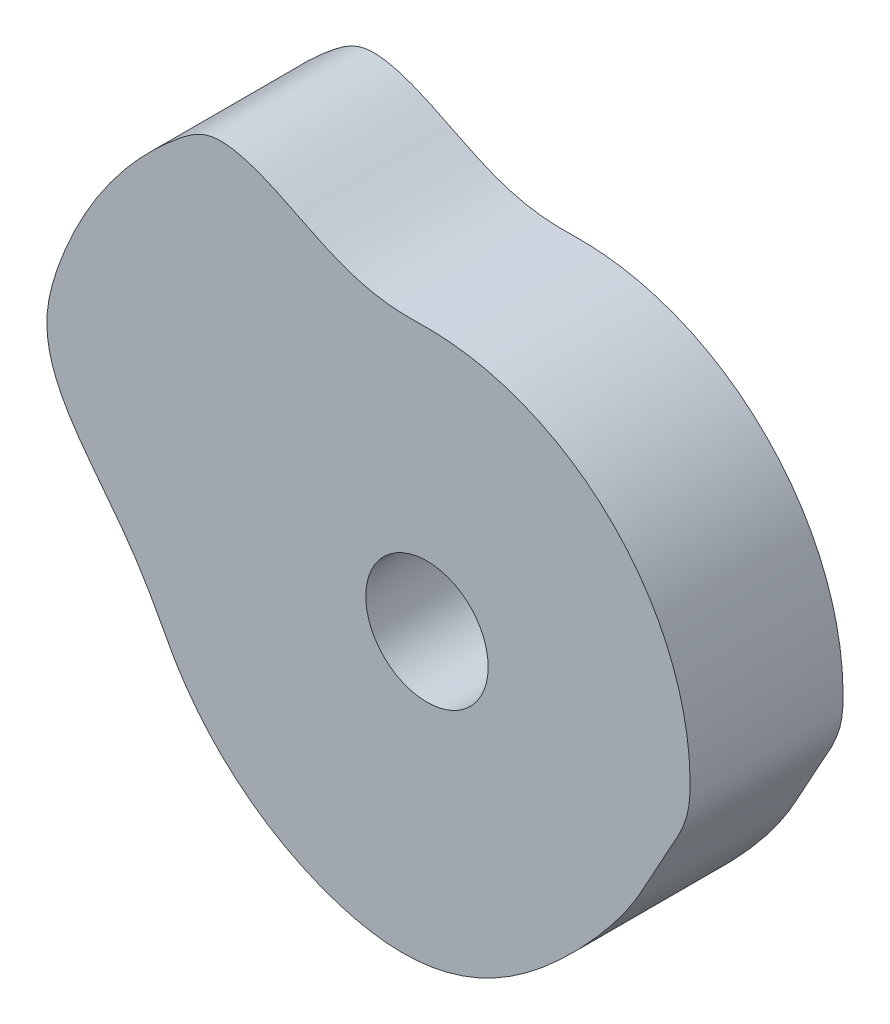
SolidWorks part; units mm, degrees
ref_plane "前视基准面" through (0, 0, 0) normal (0, 0, 1) x (1, 0, 0)
ref_plane "上视基准面" through (0, 0, 0) normal (0, 1, 0) x (1, 0, 0)
ref_plane "右视基准面" through (0, 0, 0) normal (1, 0, 0) x (0, 0, -1)
other "Configuration Table"
curve "曲线1"
sketch "草图1" plane through (0, 0, 0) normal (0, 0, 1) x (1, 0, 0)
  spline S0 degree 3 poles (0.3723, 42.999) (-0.0088, 43.0005) (-0.4074, 42.9988) (-0.8321, 42.9946) (-1.2941, 42.9895) (-1.7902, 42.9845) (-2.3194, 42.9823) (-2.8809, 42.9844) (-3.4733, 42.9934) (-4.0947, 43.0117) (-4.7431, 43.0421) (-5.4158, 43.0865) (-6.1099, 43.1475) (-6.822, 43.2268) (-7.5486, 43.3262) (-8.2858, 43.4462) (-9.0301, 43.5878) (-9.7777, 43.7508) (-10.5255, 43.9345) (-11.2705, 44.138) (-12.0104, 44.3601) (-12.7432, 44.5992) (-13.4676, 44.8538) (-14.1826, 45.1216) (-14.8878, 45.4014) (-15.5832, 45.6911) (-16.2688, 45.989) (-16.9451, 46.2936) (-17.6126, 46.6034) (-18.2719, 46.917) (-18.9237, 47.2326) (-19.5683, 47.5495) (-20.2066, 47.8659) (-20.8388, 48.1807) (-21.4653, 48.4929) (-22.0864, 48.8008) (-22.7021, 49.1035) (-23.3123, 49.3998) (-23.9171, 49.6882) (-24.5158, 49.9681) (-25.1084, 50.2376) (-25.6941, 50.4963) (-26.2722, 50.7427) (-26.8421, 50.9761) (-27.4028, 51.1954) (-27.9536, 51.3998) (-28.4933, 51.5888) (-29.0211, 51.7618) (-29.5359, 51.9181) (-30.0368, 52.0575) (-30.5227, 52.1801) (-30.9929, 52.2857) (-31.4466, 52.3748) (-31.8832, 52.4473) (-32.3023, 52.504) (-32.7036, 52.5455) (-33.0873, 52.5725) (-33.4537, 52.5858) (-33.8034, 52.5862) (-34.1374, 52.5746) (-34.4569, 52.5518) (-34.7635, 52.5182) (-35.0591, 52.4744) (-35.3455, 52.4209) (-35.6251, 52.3571) (-35.9, 52.2834) (-36.1727, 52.199) (-36.4454, 52.1033) (-36.7201, 51.9955) (-36.9992, 51.8744) (-37.2841, 51.7388) (-37.5767, 51.5877) (-37.8784, 51.4199) (-38.1902, 51.234) (-38.5133, 51.0294) (-38.8483, 50.8049) (-39.196, 50.5601) (-39.5571, 50.2945) (-39.932, 50.0077) (-40.3214, 49.6999) (-40.7256, 49.3712) (-41.1422, 49.0247) (-41.5653, 48.6666) (-41.9883, 48.302) (-42.4083, 47.9338) (-42.825, 47.5619) (-43.2383, 47.1863) (-43.6484, 46.8072) (-44.0553, 46.4246) (-44.4586, 46.0382) (-44.8588, 45.6486) (-45.2553, 45.2553) (-45.6486, 44.8588) (-46.0382, 44.4586) (-46.4246, 44.0553) (-46.8072, 43.6484) (-47.1863, 43.2383) (-47.5619, 42.825) (-47.9338, 42.4083) (-48.302, 41.9883) (-48.6666, 41.5653) (-49.0274, 41.1389) (-49.3846, 40.7096) (-49.7379, 40.277) (-50.0875, 39.8414) (-50.4334, 39.4028) (-50.7752, 38.9612) (-51.1134, 38.5167) (-51.4474, 38.0691) (-51.7778, 37.6188) (-52.1041, 37.1655) (-52.4264, 36.7093) (-52.7448, 36.2505) (-53.059, 35.7887) (-53.3694, 35.3245) (-53.6755, 34.8573) (-53.9778, 34.3877) (-54.2757, 33.9152) (-54.5697, 33.4403) (-54.8593, 32.9628) (-55.1451, 32.4829) (-55.4263, 32.0004) (-55.7035, 31.5155) (-55.9764, 31.0282) (-56.245, 30.5386) (-56.5093, 30.0465) (-56.7694, 29.5523) (-57.0251, 29.0558) (-57.2765, 28.5571) (-57.5235, 28.0561) (-57.7662, 27.5531) (-58.0044, 27.0479) (-58.2382, 26.5407) (-58.4676, 26.0315) (-58.6925, 25.5202) (-58.9131, 25.0071) (-59.129, 24.492) (-59.3406, 23.9751) (-59.5475, 23.4564) (-59.7498, 22.9358) (-59.9478, 22.4136) (-60.1405, 21.8911) (-60.3271, 21.3716) (-60.5058, 20.858) (-60.6762, 20.3517) (-60.8374, 19.8525) (-60.9898, 19.3605) (-61.1329, 18.8754) (-61.2662, 18.397) (-61.3902, 17.9252) (-61.5043, 17.4599) (-61.6087, 17.0007) (-61.7032, 16.5475) (-61.7878, 16.1) (-61.8625, 15.6578) (-61.9274, 15.2207) (-61.9825, 14.7884) (-62.0278, 14.3604) (-62.0633, 13.9363) (-62.0889, 13.5158) (-62.1049, 13.0983) (-62.1111, 12.6835) (-62.1077, 12.2709) (-62.0944, 11.8599) (-62.0712, 11.4501) (-62.0383, 11.0411) (-61.9954, 10.6324) (-61.9424, 10.2236) (-61.8794, 9.8142) (-61.806, 9.4039) (-61.7222, 8.9924) (-61.628, 8.5793) (-61.523, 8.1644) (-61.4072, 7.7475) (-61.2805, 7.3282) (-61.1427, 6.9067) (-60.9939, 6.4827) (-60.8339, 6.0561) (-60.6626, 5.6271) (-60.4802, 5.1954) (-60.2866, 4.7613) (-60.0819, 4.3247) (-59.8663, 3.8857) (-59.6397, 3.4445) (-59.4024, 3.0011) (-59.1546, 2.5557) (-58.8966, 2.1083) (-58.6286, 1.6591) (-58.351, 1.2081) (-58.064, 0.7555) (-57.7682, 0.3012) (-57.4636, -0.1543) (-57.151, -0.6115) (-56.8307, -1.0702) (-56.503, -1.5301) (-56.1686, -1.9917) (-55.8277, -2.4547) (-55.4811, -2.9192) (-55.1289, -3.3854) (-54.7721, -3.8533) (-54.4107, -4.3231) (-54.0456, -4.7949) (-53.6771, -5.2688) (-53.3058, -5.745) (-52.9324, -6.2237) (-52.5569, -6.7049) (-52.1807, -7.189) (-51.8034, -7.6757) (-51.4264, -8.1657) (-51.0497, -8.6586) (-50.6741, -9.1547) (-50.3, -9.6538) (-49.9282, -10.1561) (-49.5592, -10.6614) (-49.1932, -11.1694) (-48.8315, -11.6802) (-48.4738, -12.1931) (-48.1211, -12.7082) (-47.7739, -13.2248) (-47.4323, -13.7423) (-47.0968, -14.2603) (-46.7682, -14.7783) (-46.4461, -15.2954) (-46.1309, -15.811) (-45.8231, -16.3243) (-45.5225, -16.8346) (-45.2291, -17.3411) (-44.9431, -17.8429) (-44.664, -18.3393) (-44.3922, -18.8296) (-44.1269, -19.3128) (-43.8685, -19.7886) (-43.616, -20.2559) (-43.3698, -20.7143) (-43.1287, -21.163) (-42.8934, -21.6019) (-42.6626, -22.0299) (-42.4367, -22.4469) (-42.2149, -22.8524) (-41.997, -23.246) (-41.7828, -23.6276) (-41.5708, -23.9985) (-41.3587, -24.3621) (-41.1445, -24.7221) (-40.9272, -25.0802) (-40.7068, -25.4364) (-40.4833, -25.7907) (-40.2567, -26.143) (-40.027, -26.4933) (-39.7943, -26.8416) (-39.5586, -27.1879) (-39.3198, -27.532) (-39.0779, -27.874) (-38.8333, -28.2141) (-38.5856, -28.5518) (-38.335, -28.8875) (-38.0815, -29.2209) (-37.825, -29.5521) (-37.5657, -29.8811) (-37.3035, -30.2078) (-37.0385, -30.5322) (-36.7705, -30.8542) (-36.5, -31.1739) (-36.2265, -31.4912) (-35.9504, -31.8062) (-35.6715, -32.1187) (-35.3897, -32.4287) (-35.1055, -32.7363) (-34.8184, -33.0414) (-34.5288, -33.344) (-34.2364, -33.644) (-33.9415, -33.9415) (-33.644, -34.2364) (-33.344, -34.5288) (-33.0414, -34.8184) (-32.7363, -35.1055) (-32.4287, -35.3897) (-32.1187, -35.6715) (-31.8062, -35.9504) (-31.4912, -36.2265) (-31.1739, -36.5) (-30.8542, -36.7705) (-30.5322, -37.0385) (-30.2078, -37.3035) (-29.8811, -37.5657) (-29.5521, -37.825) (-29.2209, -38.0815) (-28.8875, -38.335) (-28.5518, -38.5856) (-28.2141, -38.8333) (-27.874, -39.0779) (-27.532, -39.3198) (-27.1879, -39.5586) (-26.8416, -39.7943) (-26.4933, -40.027) (-26.143, -40.2567) (-25.7907, -40.4833) (-25.4364, -40.7068) (-25.0802, -40.9272) (-24.7221, -41.1445) (-24.3621, -41.3587) (-24.0003, -41.5697) (-23.6367, -41.7776) (-23.2711, -41.9823) (-22.9039, -42.1837) (-22.5349, -42.382) (-22.1642, -42.577) (-21.7918, -42.7688) (-21.4177, -42.9573) (-21.0421, -43.1427) (-20.6648, -43.3246) (-20.286, -43.5034) (-19.9055, -43.6786) (-19.5237, -43.8508) (-19.1402, -44.0195) (-18.7553, -44.1847) (-18.369, -44.3468) (-17.9813, -44.5054) (-17.5923, -44.6606) (-17.2019, -44.8125) (-16.8102, -44.9609) (-16.4174, -45.1057) (-16.0242, -45.2469) (-15.6308, -45.3842) (-15.2377, -45.5174) (-14.8448, -45.6467) (-14.4522, -45.7717) (-14.0598, -45.8925) (-13.6678, -46.0093) (-13.276, -46.1215) (-12.8845, -46.2297) (-12.4934, -46.3334) (-12.1026, -46.433) (-11.7122, -46.528) (-11.3222, -46.6186) (-10.9326, -46.7048) (-10.5434, -46.7865) (-10.1546, -46.8637) (-9.7664, -46.9365) (-9.3785, -47.0045) (-8.9912, -47.0682) (-8.6044, -47.127) (-8.2181, -47.1815) (-7.8323, -47.2312) (-7.447, -47.2763) (-7.0623, -47.3167) (-6.6782, -47.3525) (-6.2947, -47.3837) (-5.9118, -47.4101) (-5.5296, -47.4317) (-5.1479, -47.4488) (-4.767, -47.4609) (-4.3866, -47.4686) (-4.007, -47.4714) (-3.628, -47.4695) (-3.2497, -47.4627) (-2.8721, -47.4515) (-2.4953, -47.4354) (-2.1192, -47.4145) (-1.7439, -47.389) (-1.3693, -47.3587) (-0.9954, -47.3237) (-0.6224, -47.284) (-0.2502, -47.2396) (0.1213, -47.1905) (0.4919, -47.1367) (0.8617, -47.0782) (1.2306, -47.015) (1.5987, -46.9471) (1.9659, -46.8748) (2.3322, -46.7976) (2.6976, -46.7161) (3.0621, -46.6297) (3.4258, -46.539) (3.7884, -46.4435) (4.1501, -46.3436) (4.5108, -46.2392) (4.8706, -46.1303) (5.2294, -46.0168) (5.5872, -45.8991) (5.9439, -45.7769) (6.2995, -45.6502) (6.6542, -45.5195) (7.0077, -45.384) (7.3602, -45.2448) (7.7116, -45.1009) (8.0619, -44.9531) (8.411, -44.8009) (8.759, -44.6447) (9.1058, -44.4845) (9.4515, -44.3202) (9.796, -44.152) (10.1393, -43.9798) (10.4813, -43.8036) (10.8222, -43.6238) (11.1618, -43.44) (11.5002, -43.2526) (11.8374, -43.0616) (12.1733, -42.8668) (12.5079, -42.6685) (12.8413, -42.4668) (13.1732, -42.2614) (13.504, -42.0529) (13.8335, -41.841) (14.1616, -41.6257) (14.4885, -41.4074) (14.814, -41.1857) (15.1383, -40.9611) (15.4612, -40.7335) (15.7827, -40.5029) (16.103, -40.2695) (16.4219, -40.0332) (16.7395, -39.7942) (17.0559, -39.5526) (17.3707, -39.3082) (17.6843, -39.0615) (17.9966, -38.8121) (18.3076, -38.5604) (18.6173, -38.3064) (18.9256, -38.0501) (19.2325, -37.7915) (19.5381, -37.5309) (19.8424, -37.2682) (20.1453, -37.0034) (20.447, -36.7368) (20.7472, -36.4682) (21.0461, -36.1979) (21.3436, -35.9258) (21.6399, -35.6521) (21.9346, -35.3767) (22.228, -35.0998) (22.52, -34.8214) (22.8106, -34.5416) (23.0998, -34.2605) (23.3875, -33.9779) (23.6738, -33.6943) (23.9586, -33.4094) (24.2419, -33.1233) (24.5236, -32.8361) (24.8039, -32.5479) (25.0825, -32.2587) (25.3596, -31.9687) (25.635, -31.6777) (25.9088, -31.3859) (26.1809, -31.0934) (26.4511, -30.7999) (26.7198, -30.506) (26.9865, -30.2113) (27.2516, -29.916) (27.5145, -29.6201) (27.7757, -29.3237) (28.0348, -29.0268) (28.2919, -28.7293) (28.547, -28.4315) (28.7999, -28.1333) (29.0507, -27.8346) (29.2993, -27.5356) (29.5456, -27.2363) (29.7896, -26.9367) (30.0312, -26.6368) (30.2706, -26.3367) (30.5071, -26.0361) (30.7415, -25.7356) (30.9731, -25.4348) (31.2021, -25.1337) (31.4284, -24.8325) (31.652, -24.5312) (31.8728, -24.2298) (32.0907, -23.9282) (32.3057, -23.6265) (32.5178, -23.3246) (32.7268, -23.0227) (32.9328, -22.7207) (33.1358, -22.4187) (33.3354, -22.1165) (33.532, -21.8144) (33.7253, -21.5122) (33.9152, -21.2099) (34.1018, -20.9076) (34.2851, -20.6054) (34.4648, -20.303) (34.6424, -19.9987) (34.8198, -19.6881) (34.9999, -19.3674) (35.184, -19.0349) (35.3721, -18.691) (35.5643, -18.3364) (35.7607, -17.9716) (35.9613, -17.5975) (36.1661, -17.215) (36.3749, -16.825) (36.5877, -16.4287) (36.8042, -16.027) (37.0241, -15.6211) (37.2468, -15.2121) (37.4723, -14.8014) (37.6995, -14.3898) (37.9284, -13.9787) (38.1577, -13.5688) (38.3874, -13.1614) (38.6162, -12.7573) (38.8434, -12.3573) (39.0685, -11.9622) (39.2907, -11.5727) (39.509, -11.1893) (39.7228, -10.8125) (39.9315, -10.4427) (40.1344, -10.0803) (40.3308, -9.7255) (40.5204, -9.3786) (40.7028, -9.0395) (40.8774, -8.7083) (41.0443, -8.3852) (41.2027, -8.0698) (41.353, -7.7621) (41.4952, -7.4621) (41.6289, -7.1691) (41.7546, -6.8829) (41.8723, -6.6032) (41.9821, -6.3292) (42.0847, -6.0606) (42.1801, -5.7965) (42.2686, -5.5361) (42.3508, -5.2787) (42.4267, -5.0231) (42.497, -4.7686) (42.5619, -4.5139) (42.6214, -4.2581) (42.6762, -4) (42.7263, -3.7385) (42.7718, -3.4725) (42.813, -3.201) (42.8499, -2.9229) (42.8826, -2.6373) (42.9111, -2.3433) (42.9358, -2.0401) (42.9562, -1.727) (42.9726, -1.4034) (42.9851, -1.0688) (42.994, -0.7229) (42.9989, -0.3653) (43.0005, 0.002) (42.9989, 0.3752) (42.994, 0.7505) (42.9859, 1.1256) (42.9743, 1.5007) (42.9597, 1.8756) (42.9417, 2.2505) (42.9203, 2.6251) (42.8959, 2.9996) (42.8679, 3.3738) (42.837, 3.7478) (42.8025, 4.1214) (42.7649, 4.4948) (42.7241, 4.8678) (42.6801, 5.2404) (42.6326, 5.6127) (42.582, 5.9845) (42.5283, 6.3559) (42.4711, 6.7268) (42.4109, 7.0971) (42.3472, 7.4669) (42.2806, 7.8362) (42.2105, 8.2049) (42.1374, 8.5729) (42.0608, 8.9403) (41.9812, 9.307) (41.8984, 9.673) (41.8125, 10.0383) (41.7232, 10.4028) (41.6308, 10.7664) (41.5353, 11.1294) (41.4366, 11.4914) (41.3349, 11.8526) (41.2297, 12.2128) (41.1217, 12.5722) (41.0103, 12.9305) (40.8959, 13.2879) (40.7784, 13.6443) (40.6578, 13.9996) (40.5341, 14.3539) (40.4073, 14.7071) (40.2774, 15.0591) (40.1445, 15.41) (40.0085, 15.7598) (39.8694, 16.1083) (39.7273, 16.4556) (39.5822, 16.8016) (39.4341, 17.1464) (39.283, 17.4899) (39.1288, 17.832) (38.9717, 18.1728) (38.8117, 18.5123) (38.6486, 18.8502) (38.4827, 19.1868) (38.3138, 19.5218) (38.142, 19.8555) (37.9672, 20.1875) (37.7896, 20.5181) (37.6091, 20.847) (37.4258, 21.1745) (37.2396, 21.5002) (37.0506, 21.8244) (36.8587, 22.1469) (36.6639, 22.4677) (36.4666, 22.7868) (36.2663, 23.1042) (36.0633, 23.4198) (35.8576, 23.7336) (35.649, 24.0456) (35.4379, 24.3558) (35.2239, 24.6641) (35.0074, 24.9706) (34.7882, 25.2751) (34.5663, 25.5777) (34.3417, 25.8783) (34.1146, 26.177) (33.8849, 26.4737) (33.6526, 26.7685) (33.4177, 27.0611) (33.1803, 27.3518) (32.9403, 27.6402) (32.698, 27.9267) (32.4528, 28.2108) (32.2056, 28.4931) (31.9556, 28.7729) (31.7033, 29.0508) (31.4486, 29.3263) (31.1915, 29.5996) (30.932, 29.8707) (30.6702, 30.1395) (30.406, 30.406) (30.1395, 30.6702) (29.8707, 30.932) (29.5996, 31.1915) (29.3263, 31.4486) (29.0508, 31.7033) (28.7729, 31.9556) (28.4931, 32.2056) (28.2108, 32.4528) (27.9267, 32.698) (27.6402, 32.9403) (27.3518, 33.1803) (27.0611, 33.4177) (26.7685, 33.6526) (26.4737, 33.8849) (26.177, 34.1146) (25.8783, 34.3417) (25.5777, 34.5663) (25.2751, 34.7882) (24.9706, 35.0074) (24.6641, 35.2239) (24.3558, 35.4379) (24.0456, 35.649) (23.7336, 35.8576) (23.4198, 36.0633) (23.1042, 36.2663) (22.7868, 36.4666) (22.4677, 36.6639) (22.1469, 36.8587) (21.8244, 37.0506) (21.5002, 37.2396) (21.1745, 37.4258) (20.847, 37.6091) (20.5181, 37.7896) (20.1875, 37.9672) (19.8555, 38.142) (19.5218, 38.3138) (19.1868, 38.4827) (18.8502, 38.6486) (18.5123, 38.8117) (18.1728, 38.9717) (17.832, 39.1288) (17.4899, 39.283) (17.1464, 39.4341) (16.8016, 39.5822) (16.4556, 39.7273) (16.1083, 39.8694) (15.7598, 40.0085) (15.41, 40.1445) (15.0591, 40.2774) (14.7071, 40.4073) (14.3539, 40.5341) (13.9996, 40.6578) (13.6443, 40.7784) (13.2879, 40.8959) (12.9305, 41.0103) (12.5722, 41.1217) (12.2128, 41.2297) (11.8526, 41.3349) (11.4914, 41.4366) (11.1294, 41.5353) (10.7664, 41.6308) (10.4028, 41.7232) (10.0383, 41.8125) (9.673, 41.8984) (9.307, 41.9812) (8.9403, 42.0608) (8.5729, 42.1374) (8.2049, 42.2105) (7.8362, 42.2806) (7.4669, 42.3472) (7.0971, 42.4109) (6.7268, 42.4711) (6.3559, 42.5283) (5.9845, 42.582) (5.6127, 42.6326) (5.2404, 42.6801) (4.8678, 42.7241) (4.4948, 42.7649) (4.1214, 42.8025) (3.7478, 42.837) (3.3738, 42.8679) (2.9996, 42.8959) (2.6251, 42.9203) (2.2505, 42.9417) (1.8756, 42.9597) (1.5007, 42.9743) (1.1256, 42.9859) (0.7505, 42.994) (0.3723, 42.999) (-0.0088, 43.0005) (-0.4074, 42.9988) knots -0.003606 -0.002413 -0.00122 0 0.001222 0.002581 0.00405 0.005628 0.007311 0.009098 0.010982 0.012961 0.015026 0.017172 0.01939 0.02167 0.024004 0.026382 0.028793 0.031228 0.033678 0.036135 0.038593 0.041044 0.043486 0.045914 0.048326 0.050721 0.053097 0.055455 0.057794 0.060115 0.062417 0.0647 0.066965 0.06921 0.071436 0.07364 0.075821 0.077978 0.080109 0.082211 0.084281 0.086317 0.088316 0.090274 0.092189 0.094058 0.095877 0.097643 0.099354 0.101007 0.1026 0.104133 0.105602 0.107009 0.108353 0.109634 0.110856 0.11202 0.11313 0.11419 0.115206 0.116184 0.117131 0.118055 0.118963 0.119865 0.120769 0.121684 0.122619 0.123583 0.124584 0.125628 0.126724 0.127876 0.129089 0.13037 0.131721 0.133145 0.134645 0.136222 0.137878 0.139613 0.141388 0.143164 0.144939 0.146715 0.14849 0.150265 0.152041 0.153816 0.155592 0.157367 0.159142 0.160918 0.162693 0.164468 0.166244 0.168019 0.169795 0.17157 0.173345 0.175121 0.176896 0.178671 0.180447 0.182222 0.183998 0.185773 0.187548 0.189324 0.191099 0.192874 0.19465 0.196425 0.1982 0.199976 0.201751 0.203527 0.205302 0.207078 0.208853 0.210628 0.212404 0.214179 0.215954 0.21773 0.219505 0.22128 0.223056 0.224831 0.226607 0.228382 0.230157 0.231933 0.233708 0.235483 0.237259 0.239034 0.24081 0.242585 0.24436 0.246136 0.247895 0.249624 0.251322 0.252989 0.254627 0.256234 0.257812 0.259363 0.260885 0.262382 0.263853 0.2653 0.266725 0.268129 0.269514 0.270881 0.272233 0.273571 0.274899 0.276216 0.277527 0.278834 0.280137 0.281441 0.282746 0.284056 0.285372 0.286696 0.28803 0.289376 0.290736 0.292111 0.293503 0.294912 0.29634 0.297788 0.299256 0.300746 0.302257 0.303789 0.305344 0.30692 0.308519 0.310139 0.311781 0.313444 0.315128 0.316831 0.318555 0.320297 0.322058 0.323836 0.325632 0.327443 0.329271 0.331114 0.332971 0.334842 0.336727 0.338623 0.340532 0.342451 0.344382 0.346322 0.348271 0.350229 0.352194 0.354167 0.356145 0.358128 0.360115 0.362105 0.364095 0.366086 0.368074 0.370059 0.372038 0.37401 0.375972 0.377923 0.379861 0.381782 0.383685 0.385569 0.38743 0.389267 0.391077 0.39286 0.394613 0.396335 0.398023 0.399678 0.401297 0.402881 0.404427 0.405934 0.407404 0.408834 0.410225 0.411577 0.412908 0.41424 0.415571 0.416903 0.418234 0.419566 0.420897 0.422229 0.42356 0.424892 0.426223 0.427555 0.428887 0.430218 0.431549 0.432881 0.434213 0.435544 0.436876 0.438207 0.439539 0.44087 0.442202 0.443533 0.444865 0.446196 0.447528 0.44886 0.450191 0.451523 0.452854 0.454186 0.455517 0.456849 0.45818 0.459512 0.460843 0.462175 0.463506 0.464838 0.466169 0.467501 0.468833 0.470164 0.471496 0.472827 0.474159 0.47549 0.476822 0.478153 0.479485 0.480816 0.482148 0.483479 0.484811 0.486143 0.487474 0.488806 0.490137 0.491469 0.4928 0.494132 0.495463 0.496795 0.498126 0.499458 0.500789 0.502121 0.503453 0.504784 0.506115 0.507447 0.508778 0.51011 0.511442 0.512773 0.514105 0.515436 0.516768 0.518099 0.519428 0.520753 0.522072 0.523387 0.524697 0.526001 0.527302 0.528597 0.529888 0.531175 0.532456 0.533734 0.535006 0.536275 0.537539 0.538799 0.540054 0.541306 0.542554 0.543797 0.545038 0.546274 0.547507 0.548737 0.549963 0.551186 0.552406 0.553623 0.554837 0.556049 0.557258 0.558465 0.559669 0.560872 0.562072 0.563271 0.564469 0.565664 0.566859 0.568053 0.569245 0.570436 0.571627 0.572818 0.574008 0.575198 0.576387 0.577577 0.578767 0.579957 0.581148 0.582339 0.583531 0.584724 0.585917 0.587112 0.588308 0.589506 0.590704 0.591904 0.593106 0.594309 0.595514 0.596721 0.597929 0.59914 0.600352 0.601567 0.602783 0.604002 0.605223 0.606446 0.607671 0.608898 0.610128 0.61136 0.612594 0.613831 0.615069 0.61631 0.617553 0.618798 0.620046 0.621295 0.622547 0.623801 0.625057 0.626315 0.627574 0.628836 0.6301 0.631365 0.632632 0.633901 0.635171 0.636443 0.637716 0.63899 0.640266 0.641543 0.642821 0.6441 0.645379 0.64666 0.647941 0.649223 0.650505 0.651787 0.65307 0.654352 0.655635 0.656917 0.658199 0.65948 0.66076 0.66204 0.663319 0.664597 0.665874 0.667149 0.668422 0.669694 0.670965 0.672233 0.673499 0.674762 0.676024 0.677282 0.678538 0.679791 0.68104 0.682287 0.68353 0.68477 0.686006 0.687238 0.688466 0.689691 0.690911 0.692127 0.693338 0.694545 0.695748 0.696945 0.698138 0.699326 0.700509 0.701686 0.702859 0.704026 0.705188 0.706345 0.707496 0.708642 0.709783 0.710917 0.712046 0.71317 0.714288 0.715401 0.71653 0.7177 0.718908 0.720154 0.721437 0.722755 0.724105 0.725486 0.726893 0.728324 0.729776 0.731244 0.732726 0.734217 0.735712 0.73721 0.738704 0.740192 0.741669 0.743133 0.744579 0.746005 0.747409 0.748787 0.750137 0.751458 0.752747 0.754004 0.755229 0.756419 0.757575 0.758697 0.759785 0.76084 0.761863 0.762856 0.76382 0.764757 0.765671 0.766562 0.767435 0.768293 0.769139 0.769977 0.770811 0.771645 0.772482 0.773327 0.774184 0.775056 0.775946 0.776859 0.777797 0.778763 0.779759 0.780789 0.781853 0.782952 0.784089 0.785263 0.786455 0.787648 0.788841 0.790034 0.791227 0.792419 0.793613 0.794805 0.795998 0.797191 0.798384 0.799577 0.800769 0.801962 0.803155 0.804348 0.805541 0.806734 0.807926 0.809119 0.810312 0.811505 0.812698 0.813891 0.815083 0.816276 0.817469 0.818662 0.819855 0.821048 0.822241 0.823433 0.824626 0.825819 0.827012 0.828205 0.829397 0.83059 0.831783 0.832976 0.834169 0.835361 0.836554 0.837747 0.83894 0.840133 0.841326 0.842519 0.843711 0.844904 0.846097 0.84729 0.848483 0.849676 0.850868 0.852061 0.853254 0.854447 0.85564 0.856833 0.858025 0.859218 0.860411 0.861604 0.862797 0.86399 0.865182 0.866375 0.867568 0.868761 0.869954 0.871147 0.872339 0.873532 0.874725 0.875918 0.877111 0.878304 0.879496 0.880689 0.881882 0.883075 0.884268 0.885461 0.886653 0.887846 0.889039 0.890232 0.891425 0.892617 0.89381 0.895003 0.896196 0.897389 0.898582 0.899774 0.900967 0.90216 0.903353 0.904546 0.905739 0.906931 0.908124 0.909317 0.91051 0.911703 0.912895 0.914088 0.915281 0.916474 0.917667 0.91886 0.920053 0.921245 0.922438 0.923631 0.924824 0.926017 0.92721 0.928402 0.929595 0.930788 0.931981 0.933174 0.934367 0.935559 0.936752 0.937945 0.939138 0.940331 0.941524 0.942716 0.943909 0.945102 0.946295 0.947488 0.94868 0.949874 0.951066 0.952259 0.953452 0.954645 0.955838 0.95703 0.958223 0.959416 0.960609 0.961802 0.962994 0.964187 0.96538 0.966573 0.967766 0.968959 0.970152 0.971344 0.972537 0.97373 0.974923 0.976116 0.977309 0.978501 0.979694 0.980887 0.98208 0.983273 0.984466 0.985658 0.986851 0.988044 0.989237 0.99043 0.991622 0.992816 0.994008 0.995201 0.996394 0.997587 0.99878 1 1.001222 1.002581 1.00405 only from (-0.0087, 43) to (-0.0087, 43) construction
  spline S1 degree 3 poles (0.3723, 42.999) (-0.0088, 43.0005) (-0.4074, 42.9988) (-0.8321, 42.9946) (-1.2941, 42.9895) (-1.7902, 42.9845) (-2.3194, 42.9823) (-2.8809, 42.9844) (-3.4733, 42.9934) (-4.0947, 43.0117) (-4.7431, 43.0421) (-5.4158, 43.0865) (-6.1099, 43.1475) (-6.822, 43.2268) (-7.5486, 43.3262) (-8.2858, 43.4462) (-9.0301, 43.5878) (-9.7777, 43.7508) (-10.5255, 43.9345) (-11.2705, 44.138) (-12.0104, 44.3601) (-12.7432, 44.5992) (-13.4676, 44.8538) (-14.1826, 45.1216) (-14.8878, 45.4014) (-15.5832, 45.6911) (-16.2688, 45.989) (-16.9451, 46.2936) (-17.6126, 46.6034) (-18.2719, 46.917) (-18.9237, 47.2326) (-19.5683, 47.5495) (-20.2066, 47.8659) (-20.8388, 48.1807) (-21.4653, 48.4929) (-22.0864, 48.8008) (-22.7021, 49.1035) (-23.3123, 49.3998) (-23.9171, 49.6882) (-24.5158, 49.9681) (-25.1084, 50.2376) (-25.6941, 50.4963) (-26.2722, 50.7427) (-26.8421, 50.9761) (-27.4028, 51.1954) (-27.9536, 51.3998) (-28.4933, 51.5888) (-29.0211, 51.7618) (-29.5359, 51.9181) (-30.0368, 52.0575) (-30.5227, 52.1801) (-30.9929, 52.2857) (-31.4466, 52.3748) (-31.8832, 52.4473) (-32.3023, 52.504) (-32.7036, 52.5455) (-33.0873, 52.5725) (-33.4537, 52.5858) (-33.8034, 52.5862) (-34.1374, 52.5746) (-34.4569, 52.5518) (-34.7635, 52.5182) (-35.0591, 52.4744) (-35.3455, 52.4209) (-35.6251, 52.3571) (-35.9, 52.2834) (-36.1727, 52.199) (-36.4454, 52.1033) (-36.7201, 51.9955) (-36.9992, 51.8744) (-37.2841, 51.7388) (-37.5767, 51.5877) (-37.8784, 51.4199) (-38.1902, 51.234) (-38.5133, 51.0294) (-38.8483, 50.8049) (-39.196, 50.5601) (-39.5571, 50.2945) (-39.932, 50.0077) (-40.3214, 49.6999) (-40.7256, 49.3712) (-41.1422, 49.0247) (-41.5653, 48.6666) (-41.9883, 48.302) (-42.4083, 47.9338) (-42.825, 47.5619) (-43.2383, 47.1863) (-43.6484, 46.8072) (-44.0553, 46.4246) (-44.4586, 46.0382) (-44.8588, 45.6486) (-45.2553, 45.2553) (-45.6486, 44.8588) (-46.0382, 44.4586) (-46.4246, 44.0553) (-46.8072, 43.6484) (-47.1863, 43.2383) (-47.5619, 42.825) (-47.9338, 42.4083) (-48.302, 41.9883) (-48.6666, 41.5653) (-49.0274, 41.1389) (-49.3846, 40.7096) (-49.7379, 40.277) (-50.0875, 39.8414) (-50.4334, 39.4028) (-50.7752, 38.9612) (-51.1134, 38.5167) (-51.4474, 38.0691) (-51.7778, 37.6188) (-52.1041, 37.1655) (-52.4264, 36.7093) (-52.7448, 36.2505) (-53.059, 35.7887) (-53.3694, 35.3245) (-53.6755, 34.8573) (-53.9778, 34.3877) (-54.2757, 33.9152) (-54.5697, 33.4403) (-54.8593, 32.9628) (-55.1451, 32.4829) (-55.4263, 32.0004) (-55.7035, 31.5155) (-55.9764, 31.0282) (-56.245, 30.5386) (-56.5093, 30.0465) (-56.7694, 29.5523) (-57.0251, 29.0558) (-57.2765, 28.5571) (-57.5235, 28.0561) (-57.7662, 27.5531) (-58.0044, 27.0479) (-58.2382, 26.5407) (-58.4676, 26.0315) (-58.6925, 25.5202) (-58.9131, 25.0071) (-59.129, 24.492) (-59.3406, 23.9751) (-59.5475, 23.4564) (-59.7498, 22.9358) (-59.9478, 22.4136) (-60.1405, 21.8911) (-60.3271, 21.3716) (-60.5058, 20.858) (-60.6762, 20.3517) (-60.8374, 19.8525) (-60.9898, 19.3605) (-61.1329, 18.8754) (-61.2662, 18.397) (-61.3902, 17.9252) (-61.5043, 17.4599) (-61.6087, 17.0007) (-61.7032, 16.5475) (-61.7878, 16.1) (-61.8625, 15.6578) (-61.9274, 15.2207) (-61.9825, 14.7884) (-62.0278, 14.3604) (-62.0633, 13.9363) (-62.0889, 13.5158) (-62.1049, 13.0983) (-62.1111, 12.6835) (-62.1077, 12.2709) (-62.0944, 11.8599) (-62.0712, 11.4501) (-62.0383, 11.0411) (-61.9954, 10.6324) (-61.9424, 10.2236) (-61.8794, 9.8142) (-61.806, 9.4039) (-61.7222, 8.9924) (-61.628, 8.5793) (-61.523, 8.1644) (-61.4072, 7.7475) (-61.2805, 7.3282) (-61.1427, 6.9067) (-60.9939, 6.4827) (-60.8339, 6.0561) (-60.6626, 5.6271) (-60.4802, 5.1954) (-60.2866, 4.7613) (-60.0819, 4.3247) (-59.8663, 3.8857) (-59.6397, 3.4445) (-59.4024, 3.0011) (-59.1546, 2.5557) (-58.8966, 2.1083) (-58.6286, 1.6591) (-58.351, 1.2081) (-58.064, 0.7555) (-57.7682, 0.3012) (-57.4636, -0.1543) (-57.151, -0.6115) (-56.8307, -1.0702) (-56.503, -1.5301) (-56.1686, -1.9917) (-55.8277, -2.4547) (-55.4811, -2.9192) (-55.1289, -3.3854) (-54.7721, -3.8533) (-54.4107, -4.3231) (-54.0456, -4.7949) (-53.6771, -5.2688) (-53.3058, -5.745) (-52.9324, -6.2237) (-52.5569, -6.7049) (-52.1807, -7.189) (-51.8034, -7.6757) (-51.4264, -8.1657) (-51.0497, -8.6586) (-50.6741, -9.1547) (-50.3, -9.6538) (-49.9282, -10.1561) (-49.5592, -10.6614) (-49.1932, -11.1694) (-48.8315, -11.6802) (-48.4738, -12.1931) (-48.1211, -12.7082) (-47.7739, -13.2248) (-47.4323, -13.7423) (-47.0968, -14.2603) (-46.7682, -14.7783) (-46.4461, -15.2954) (-46.1309, -15.811) (-45.8231, -16.3243) (-45.5225, -16.8346) (-45.2291, -17.3411) (-44.9431, -17.8429) (-44.664, -18.3393) (-44.3922, -18.8296) (-44.1269, -19.3128) (-43.8685, -19.7886) (-43.616, -20.2559) (-43.3698, -20.7143) (-43.1287, -21.163) (-42.8934, -21.6019) (-42.6626, -22.0299) (-42.4367, -22.4469) (-42.2149, -22.8524) (-41.997, -23.246) (-41.7828, -23.6276) (-41.5708, -23.9985) (-41.3587, -24.3621) (-41.1445, -24.7221) (-40.9272, -25.0802) (-40.7068, -25.4364) (-40.4833, -25.7907) (-40.2567, -26.143) (-40.027, -26.4933) (-39.7943, -26.8416) (-39.5586, -27.1879) (-39.3198, -27.532) (-39.0779, -27.874) (-38.8333, -28.2141) (-38.5856, -28.5518) (-38.335, -28.8875) (-38.0815, -29.2209) (-37.825, -29.5521) (-37.5657, -29.8811) (-37.3035, -30.2078) (-37.0385, -30.5322) (-36.7705, -30.8542) (-36.5, -31.1739) (-36.2265, -31.4912) (-35.9504, -31.8062) (-35.6715, -32.1187) (-35.3897, -32.4287) (-35.1055, -32.7363) (-34.8184, -33.0414) (-34.5288, -33.344) (-34.2364, -33.644) (-33.9415, -33.9415) (-33.644, -34.2364) (-33.344, -34.5288) (-33.0414, -34.8184) (-32.7363, -35.1055) (-32.4287, -35.3897) (-32.1187, -35.6715) (-31.8062, -35.9504) (-31.4912, -36.2265) (-31.1739, -36.5) (-30.8542, -36.7705) (-30.5322, -37.0385) (-30.2078, -37.3035) (-29.8811, -37.5657) (-29.5521, -37.825) (-29.2209, -38.0815) (-28.8875, -38.335) (-28.5518, -38.5856) (-28.2141, -38.8333) (-27.874, -39.0779) (-27.532, -39.3198) (-27.1879, -39.5586) (-26.8416, -39.7943) (-26.4933, -40.027) (-26.143, -40.2567) (-25.7907, -40.4833) (-25.4364, -40.7068) (-25.0802, -40.9272) (-24.7221, -41.1445) (-24.3621, -41.3587) (-24.0003, -41.5697) (-23.6367, -41.7776) (-23.2711, -41.9823) (-22.9039, -42.1837) (-22.5349, -42.382) (-22.1642, -42.577) (-21.7918, -42.7688) (-21.4177, -42.9573) (-21.0421, -43.1427) (-20.6648, -43.3246) (-20.286, -43.5034) (-19.9055, -43.6786) (-19.5237, -43.8508) (-19.1402, -44.0195) (-18.7553, -44.1847) (-18.369, -44.3468) (-17.9813, -44.5054) (-17.5923, -44.6606) (-17.2019, -44.8125) (-16.8102, -44.9609) (-16.4174, -45.1057) (-16.0242, -45.2469) (-15.6308, -45.3842) (-15.2377, -45.5174) (-14.8448, -45.6467) (-14.4522, -45.7717) (-14.0598, -45.8925) (-13.6678, -46.0093) (-13.276, -46.1215) (-12.8845, -46.2297) (-12.4934, -46.3334) (-12.1026, -46.433) (-11.7122, -46.528) (-11.3222, -46.6186) (-10.9326, -46.7048) (-10.5434, -46.7865) (-10.1546, -46.8637) (-9.7664, -46.9365) (-9.3785, -47.0045) (-8.9912, -47.0682) (-8.6044, -47.127) (-8.2181, -47.1815) (-7.8323, -47.2312) (-7.447, -47.2763) (-7.0623, -47.3167) (-6.6782, -47.3525) (-6.2947, -47.3837) (-5.9118, -47.4101) (-5.5296, -47.4317) (-5.1479, -47.4488) (-4.767, -47.4609) (-4.3866, -47.4686) (-4.007, -47.4714) (-3.628, -47.4695) (-3.2497, -47.4627) (-2.8721, -47.4515) (-2.4953, -47.4354) (-2.1192, -47.4145) (-1.7439, -47.389) (-1.3693, -47.3587) (-0.9954, -47.3237) (-0.6224, -47.284) (-0.2502, -47.2396) (0.1213, -47.1905) (0.4919, -47.1367) (0.8617, -47.0782) (1.2306, -47.015) (1.5987, -46.9471) (1.9659, -46.8748) (2.3322, -46.7976) (2.6976, -46.7161) (3.0621, -46.6297) (3.4258, -46.539) (3.7884, -46.4435) (4.1501, -46.3436) (4.5108, -46.2392) (4.8706, -46.1303) (5.2294, -46.0168) (5.5872, -45.8991) (5.9439, -45.7769) (6.2995, -45.6502) (6.6542, -45.5195) (7.0077, -45.384) (7.3602, -45.2448) (7.7116, -45.1009) (8.0619, -44.9531) (8.411, -44.8009) (8.759, -44.6447) (9.1058, -44.4845) (9.4515, -44.3202) (9.796, -44.152) (10.1393, -43.9798) (10.4813, -43.8036) (10.8222, -43.6238) (11.1618, -43.44) (11.5002, -43.2526) (11.8374, -43.0616) (12.1733, -42.8668) (12.5079, -42.6685) (12.8413, -42.4668) (13.1732, -42.2614) (13.504, -42.0529) (13.8335, -41.841) (14.1616, -41.6257) (14.4885, -41.4074) (14.814, -41.1857) (15.1383, -40.9611) (15.4612, -40.7335) (15.7827, -40.5029) (16.103, -40.2695) (16.4219, -40.0332) (16.7395, -39.7942) (17.0559, -39.5526) (17.3707, -39.3082) (17.6843, -39.0615) (17.9966, -38.8121) (18.3076, -38.5604) (18.6173, -38.3064) (18.9256, -38.0501) (19.2325, -37.7915) (19.5381, -37.5309) (19.8424, -37.2682) (20.1453, -37.0034) (20.447, -36.7368) (20.7472, -36.4682) (21.0461, -36.1979) (21.3436, -35.9258) (21.6399, -35.6521) (21.9346, -35.3767) (22.228, -35.0998) (22.52, -34.8214) (22.8106, -34.5416) (23.0998, -34.2605) (23.3875, -33.9779) (23.6738, -33.6943) (23.9586, -33.4094) (24.2419, -33.1233) (24.5236, -32.8361) (24.8039, -32.5479) (25.0825, -32.2587) (25.3596, -31.9687) (25.635, -31.6777) (25.9088, -31.3859) (26.1809, -31.0934) (26.4511, -30.7999) (26.7198, -30.506) (26.9865, -30.2113) (27.2516, -29.916) (27.5145, -29.6201) (27.7757, -29.3237) (28.0348, -29.0268) (28.2919, -28.7293) (28.547, -28.4315) (28.7999, -28.1333) (29.0507, -27.8346) (29.2993, -27.5356) (29.5456, -27.2363) (29.7896, -26.9367) (30.0312, -26.6368) (30.2706, -26.3367) (30.5071, -26.0361) (30.7415, -25.7356) (30.9731, -25.4348) (31.2021, -25.1337) (31.4284, -24.8325) (31.652, -24.5312) (31.8728, -24.2298) (32.0907, -23.9282) (32.3057, -23.6265) (32.5178, -23.3246) (32.7268, -23.0227) (32.9328, -22.7207) (33.1358, -22.4187) (33.3354, -22.1165) (33.532, -21.8144) (33.7253, -21.5122) (33.9152, -21.2099) (34.1018, -20.9076) (34.2851, -20.6054) (34.4648, -20.303) (34.6424, -19.9987) (34.8198, -19.6881) (34.9999, -19.3674) (35.184, -19.0349) (35.3721, -18.691) (35.5643, -18.3364) (35.7607, -17.9716) (35.9613, -17.5975) (36.1661, -17.215) (36.3749, -16.825) (36.5877, -16.4287) (36.8042, -16.027) (37.0241, -15.6211) (37.2468, -15.2121) (37.4723, -14.8014) (37.6995, -14.3898) (37.9284, -13.9787) (38.1577, -13.5688) (38.3874, -13.1614) (38.6162, -12.7573) (38.8434, -12.3573) (39.0685, -11.9622) (39.2907, -11.5727) (39.509, -11.1893) (39.7228, -10.8125) (39.9315, -10.4427) (40.1344, -10.0803) (40.3308, -9.7255) (40.5204, -9.3786) (40.7028, -9.0395) (40.8774, -8.7083) (41.0443, -8.3852) (41.2027, -8.0698) (41.353, -7.7621) (41.4952, -7.4621) (41.6289, -7.1691) (41.7546, -6.8829) (41.8723, -6.6032) (41.9821, -6.3292) (42.0847, -6.0606) (42.1801, -5.7965) (42.2686, -5.5361) (42.3508, -5.2787) (42.4267, -5.0231) (42.497, -4.7686) (42.5619, -4.5139) (42.6214, -4.2581) (42.6762, -4) (42.7263, -3.7385) (42.7718, -3.4725) (42.813, -3.201) (42.8499, -2.9229) (42.8826, -2.6373) (42.9111, -2.3433) (42.9358, -2.0401) (42.9562, -1.727) (42.9726, -1.4034) (42.9851, -1.0688) (42.994, -0.7229) (42.9989, -0.3653) (43.0005, 0.002) (42.9989, 0.3752) (42.994, 0.7505) (42.9859, 1.1256) (42.9743, 1.5007) (42.9597, 1.8756) (42.9417, 2.2505) (42.9203, 2.6251) (42.8959, 2.9996) (42.8679, 3.3738) (42.837, 3.7478) (42.8025, 4.1214) (42.7649, 4.4948) (42.7241, 4.8678) (42.6801, 5.2404) (42.6326, 5.6127) (42.582, 5.9845) (42.5283, 6.3559) (42.4711, 6.7268) (42.4109, 7.0971) (42.3472, 7.4669) (42.2806, 7.8362) (42.2105, 8.2049) (42.1374, 8.5729) (42.0608, 8.9403) (41.9812, 9.307) (41.8984, 9.673) (41.8125, 10.0383) (41.7232, 10.4028) (41.6308, 10.7664) (41.5353, 11.1294) (41.4366, 11.4914) (41.3349, 11.8526) (41.2297, 12.2128) (41.1217, 12.5722) (41.0103, 12.9305) (40.8959, 13.2879) (40.7784, 13.6443) (40.6578, 13.9996) (40.5341, 14.3539) (40.4073, 14.7071) (40.2774, 15.0591) (40.1445, 15.41) (40.0085, 15.7598) (39.8694, 16.1083) (39.7273, 16.4556) (39.5822, 16.8016) (39.4341, 17.1464) (39.283, 17.4899) (39.1288, 17.832) (38.9717, 18.1728) (38.8117, 18.5123) (38.6486, 18.8502) (38.4827, 19.1868) (38.3138, 19.5218) (38.142, 19.8555) (37.9672, 20.1875) (37.7896, 20.5181) (37.6091, 20.847) (37.4258, 21.1745) (37.2396, 21.5002) (37.0506, 21.8244) (36.8587, 22.1469) (36.6639, 22.4677) (36.4666, 22.7868) (36.2663, 23.1042) (36.0633, 23.4198) (35.8576, 23.7336) (35.649, 24.0456) (35.4379, 24.3558) (35.2239, 24.6641) (35.0074, 24.9706) (34.7882, 25.2751) (34.5663, 25.5777) (34.3417, 25.8783) (34.1146, 26.177) (33.8849, 26.4737) (33.6526, 26.7685) (33.4177, 27.0611) (33.1803, 27.3518) (32.9403, 27.6402) (32.698, 27.9267) (32.4528, 28.2108) (32.2056, 28.4931) (31.9556, 28.7729) (31.7033, 29.0508) (31.4486, 29.3263) (31.1915, 29.5996) (30.932, 29.8707) (30.6702, 30.1395) (30.406, 30.406) (30.1395, 30.6702) (29.8707, 30.932) (29.5996, 31.1915) (29.3263, 31.4486) (29.0508, 31.7033) (28.7729, 31.9556) (28.4931, 32.2056) (28.2108, 32.4528) (27.9267, 32.698) (27.6402, 32.9403) (27.3518, 33.1803) (27.0611, 33.4177) (26.7685, 33.6526) (26.4737, 33.8849) (26.177, 34.1146) (25.8783, 34.3417) (25.5777, 34.5663) (25.2751, 34.7882) (24.9706, 35.0074) (24.6641, 35.2239) (24.3558, 35.4379) (24.0456, 35.649) (23.7336, 35.8576) (23.4198, 36.0633) (23.1042, 36.2663) (22.7868, 36.4666) (22.4677, 36.6639) (22.1469, 36.8587) (21.8244, 37.0506) (21.5002, 37.2396) (21.1745, 37.4258) (20.847, 37.6091) (20.5181, 37.7896) (20.1875, 37.9672) (19.8555, 38.142) (19.5218, 38.3138) (19.1868, 38.4827) (18.8502, 38.6486) (18.5123, 38.8117) (18.1728, 38.9717) (17.832, 39.1288) (17.4899, 39.283) (17.1464, 39.4341) (16.8016, 39.5822) (16.4556, 39.7273) (16.1083, 39.8694) (15.7598, 40.0085) (15.41, 40.1445) (15.0591, 40.2774) (14.7071, 40.4073) (14.3539, 40.5341) (13.9996, 40.6578) (13.6443, 40.7784) (13.2879, 40.8959) (12.9305, 41.0103) (12.5722, 41.1217) (12.2128, 41.2297) (11.8526, 41.3349) (11.4914, 41.4366) (11.1294, 41.5353) (10.7664, 41.6308) (10.4028, 41.7232) (10.0383, 41.8125) (9.673, 41.8984) (9.307, 41.9812) (8.9403, 42.0608) (8.5729, 42.1374) (8.2049, 42.2105) (7.8362, 42.2806) (7.4669, 42.3472) (7.0971, 42.4109) (6.7268, 42.4711) (6.3559, 42.5283) (5.9845, 42.582) (5.6127, 42.6326) (5.2404, 42.6801) (4.8678, 42.7241) (4.4948, 42.7649) (4.1214, 42.8025) (3.7478, 42.837) (3.3738, 42.8679) (2.9996, 42.8959) (2.6251, 42.9203) (2.2505, 42.9417) (1.8756, 42.9597) (1.5007, 42.9743) (1.1256, 42.9859) (0.7505, 42.994) (0.3723, 42.999) (-0.0088, 43.0005) (-0.4074, 42.9988) knots -0.003606 -0.002413 -0.00122 0 0.001222 0.002581 0.00405 0.005628 0.007311 0.009098 0.010982 0.012961 0.015026 0.017172 0.01939 0.02167 0.024004 0.026382 0.028793 0.031228 0.033678 0.036135 0.038593 0.041044 0.043486 0.045914 0.048326 0.050721 0.053097 0.055455 0.057794 0.060115 0.062417 0.0647 0.066965 0.06921 0.071436 0.07364 0.075821 0.077978 0.080109 0.082211 0.084281 0.086317 0.088316 0.090274 0.092189 0.094058 0.095877 0.097643 0.099354 0.101007 0.1026 0.104133 0.105602 0.107009 0.108353 0.109634 0.110856 0.11202 0.11313 0.11419 0.115206 0.116184 0.117131 0.118055 0.118963 0.119865 0.120769 0.121684 0.122619 0.123583 0.124584 0.125628 0.126724 0.127876 0.129089 0.13037 0.131721 0.133145 0.134645 0.136222 0.137878 0.139613 0.141388 0.143164 0.144939 0.146715 0.14849 0.150265 0.152041 0.153816 0.155592 0.157367 0.159142 0.160918 0.162693 0.164468 0.166244 0.168019 0.169795 0.17157 0.173345 0.175121 0.176896 0.178671 0.180447 0.182222 0.183998 0.185773 0.187548 0.189324 0.191099 0.192874 0.19465 0.196425 0.1982 0.199976 0.201751 0.203527 0.205302 0.207078 0.208853 0.210628 0.212404 0.214179 0.215954 0.21773 0.219505 0.22128 0.223056 0.224831 0.226607 0.228382 0.230157 0.231933 0.233708 0.235483 0.237259 0.239034 0.24081 0.242585 0.24436 0.246136 0.247895 0.249624 0.251322 0.252989 0.254627 0.256234 0.257812 0.259363 0.260885 0.262382 0.263853 0.2653 0.266725 0.268129 0.269514 0.270881 0.272233 0.273571 0.274899 0.276216 0.277527 0.278834 0.280137 0.281441 0.282746 0.284056 0.285372 0.286696 0.28803 0.289376 0.290736 0.292111 0.293503 0.294912 0.29634 0.297788 0.299256 0.300746 0.302257 0.303789 0.305344 0.30692 0.308519 0.310139 0.311781 0.313444 0.315128 0.316831 0.318555 0.320297 0.322058 0.323836 0.325632 0.327443 0.329271 0.331114 0.332971 0.334842 0.336727 0.338623 0.340532 0.342451 0.344382 0.346322 0.348271 0.350229 0.352194 0.354167 0.356145 0.358128 0.360115 0.362105 0.364095 0.366086 0.368074 0.370059 0.372038 0.37401 0.375972 0.377923 0.379861 0.381782 0.383685 0.385569 0.38743 0.389267 0.391077 0.39286 0.394613 0.396335 0.398023 0.399678 0.401297 0.402881 0.404427 0.405934 0.407404 0.408834 0.410225 0.411577 0.412908 0.41424 0.415571 0.416903 0.418234 0.419566 0.420897 0.422229 0.42356 0.424892 0.426223 0.427555 0.428887 0.430218 0.431549 0.432881 0.434213 0.435544 0.436876 0.438207 0.439539 0.44087 0.442202 0.443533 0.444865 0.446196 0.447528 0.44886 0.450191 0.451523 0.452854 0.454186 0.455517 0.456849 0.45818 0.459512 0.460843 0.462175 0.463506 0.464838 0.466169 0.467501 0.468833 0.470164 0.471496 0.472827 0.474159 0.47549 0.476822 0.478153 0.479485 0.480816 0.482148 0.483479 0.484811 0.486143 0.487474 0.488806 0.490137 0.491469 0.4928 0.494132 0.495463 0.496795 0.498126 0.499458 0.500789 0.502121 0.503453 0.504784 0.506115 0.507447 0.508778 0.51011 0.511442 0.512773 0.514105 0.515436 0.516768 0.518099 0.519428 0.520753 0.522072 0.523387 0.524697 0.526001 0.527302 0.528597 0.529888 0.531175 0.532456 0.533734 0.535006 0.536275 0.537539 0.538799 0.540054 0.541306 0.542554 0.543797 0.545038 0.546274 0.547507 0.548737 0.549963 0.551186 0.552406 0.553623 0.554837 0.556049 0.557258 0.558465 0.559669 0.560872 0.562072 0.563271 0.564469 0.565664 0.566859 0.568053 0.569245 0.570436 0.571627 0.572818 0.574008 0.575198 0.576387 0.577577 0.578767 0.579957 0.581148 0.582339 0.583531 0.584724 0.585917 0.587112 0.588308 0.589506 0.590704 0.591904 0.593106 0.594309 0.595514 0.596721 0.597929 0.59914 0.600352 0.601567 0.602783 0.604002 0.605223 0.606446 0.607671 0.608898 0.610128 0.61136 0.612594 0.613831 0.615069 0.61631 0.617553 0.618798 0.620046 0.621295 0.622547 0.623801 0.625057 0.626315 0.627574 0.628836 0.6301 0.631365 0.632632 0.633901 0.635171 0.636443 0.637716 0.63899 0.640266 0.641543 0.642821 0.6441 0.645379 0.64666 0.647941 0.649223 0.650505 0.651787 0.65307 0.654352 0.655635 0.656917 0.658199 0.65948 0.66076 0.66204 0.663319 0.664597 0.665874 0.667149 0.668422 0.669694 0.670965 0.672233 0.673499 0.674762 0.676024 0.677282 0.678538 0.679791 0.68104 0.682287 0.68353 0.68477 0.686006 0.687238 0.688466 0.689691 0.690911 0.692127 0.693338 0.694545 0.695748 0.696945 0.698138 0.699326 0.700509 0.701686 0.702859 0.704026 0.705188 0.706345 0.707496 0.708642 0.709783 0.710917 0.712046 0.71317 0.714288 0.715401 0.71653 0.7177 0.718908 0.720154 0.721437 0.722755 0.724105 0.725486 0.726893 0.728324 0.729776 0.731244 0.732726 0.734217 0.735712 0.73721 0.738704 0.740192 0.741669 0.743133 0.744579 0.746005 0.747409 0.748787 0.750137 0.751458 0.752747 0.754004 0.755229 0.756419 0.757575 0.758697 0.759785 0.76084 0.761863 0.762856 0.76382 0.764757 0.765671 0.766562 0.767435 0.768293 0.769139 0.769977 0.770811 0.771645 0.772482 0.773327 0.774184 0.775056 0.775946 0.776859 0.777797 0.778763 0.779759 0.780789 0.781853 0.782952 0.784089 0.785263 0.786455 0.787648 0.788841 0.790034 0.791227 0.792419 0.793613 0.794805 0.795998 0.797191 0.798384 0.799577 0.800769 0.801962 0.803155 0.804348 0.805541 0.806734 0.807926 0.809119 0.810312 0.811505 0.812698 0.813891 0.815083 0.816276 0.817469 0.818662 0.819855 0.821048 0.822241 0.823433 0.824626 0.825819 0.827012 0.828205 0.829397 0.83059 0.831783 0.832976 0.834169 0.835361 0.836554 0.837747 0.83894 0.840133 0.841326 0.842519 0.843711 0.844904 0.846097 0.84729 0.848483 0.849676 0.850868 0.852061 0.853254 0.854447 0.85564 0.856833 0.858025 0.859218 0.860411 0.861604 0.862797 0.86399 0.865182 0.866375 0.867568 0.868761 0.869954 0.871147 0.872339 0.873532 0.874725 0.875918 0.877111 0.878304 0.879496 0.880689 0.881882 0.883075 0.884268 0.885461 0.886653 0.887846 0.889039 0.890232 0.891425 0.892617 0.89381 0.895003 0.896196 0.897389 0.898582 0.899774 0.900967 0.90216 0.903353 0.904546 0.905739 0.906931 0.908124 0.909317 0.91051 0.911703 0.912895 0.914088 0.915281 0.916474 0.917667 0.91886 0.920053 0.921245 0.922438 0.923631 0.924824 0.926017 0.92721 0.928402 0.929595 0.930788 0.931981 0.933174 0.934367 0.935559 0.936752 0.937945 0.939138 0.940331 0.941524 0.942716 0.943909 0.945102 0.946295 0.947488 0.94868 0.949874 0.951066 0.952259 0.953452 0.954645 0.955838 0.95703 0.958223 0.959416 0.960609 0.961802 0.962994 0.964187 0.96538 0.966573 0.967766 0.968959 0.970152 0.971344 0.972537 0.97373 0.974923 0.976116 0.977309 0.978501 0.979694 0.980887 0.98208 0.983273 0.984466 0.985658 0.986851 0.988044 0.989237 0.99043 0.991622 0.992816 0.994008 0.995201 0.996394 0.997587 0.99878 1 1.001222 1.002581 1.00405 only from (-0.0087, 43) to (-0.0087, 43)
extrude "凸台-拉伸1" add sketch "草图1" along normal blind 25
sketch "草图2" plane through (0, 0, 0) normal (0, 0, 1) x (1, 0, 0)
  circle A0 centre (0, 0) radius 10
extrude "切除-拉伸1" cut sketch "草图2" along normal blind 25 contours A0
sketch "草图3" plane through (0, 0, 25) normal (0, 0, 1) x (1, 0, 0)
  point P0 (0, 53)
sketch "草图4" plane through (0, 0, 0) normal (0, 0, -1) x (-1, 0, 0)
  point P0 (0, 53)
sketch "草图5" plane through (0, 0, 0) normal (1, 0, 0) x (0, 0, -1)
  line L0 (-25, 53) -> (0, 53) construction
  point P4 (-12.5, 53)
sketch "草图7" plane through (0, 0, 0) normal (0, 1, 0) x (1, 0, 0)
  line L0 (0, 0) -> (0, -25) construction
